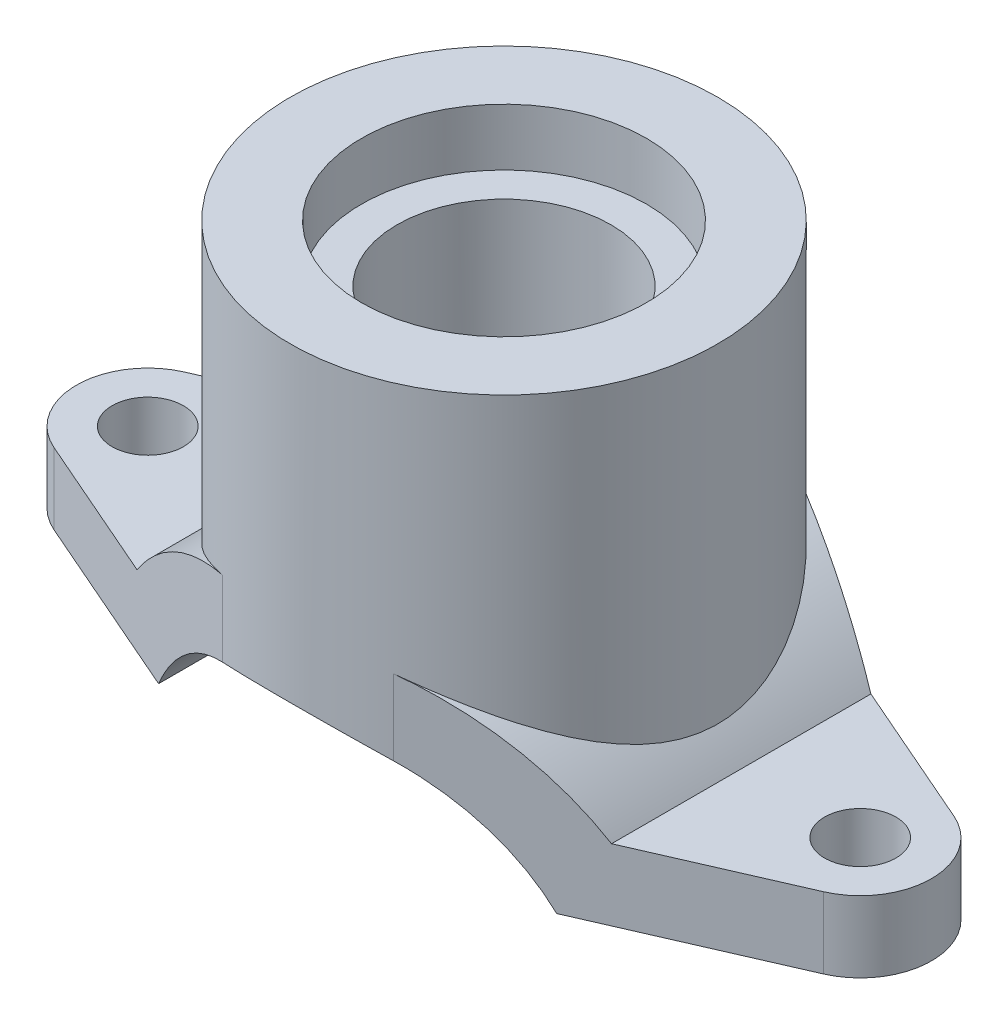
SolidWorks part; units mm, degrees
material "AISI 304"
ref_plane "Front Plane" through (0, 0, 0) normal (0, 0, 1) x (1, 0, 0)
ref_plane "Top Plane" through (0, 0, 0) normal (0, 1, 0) x (1, 0, 0)
ref_plane "Right Plane" through (0, 0, 0) normal (1, 0, 0) x (0, 0, -1)
sketch "Sketch2" plane through (0, 0, 0) normal (0, 0, 1) x (1, 0, 0)
  line L0 (0, 0) -> (0, 135.9633) construction
  line L1 (-150, 0) -> (-69.8498, 0)
  line L2 (69.8498, 0) -> (150, 0)
  line L3 (-150, 25) -> (-83.2406, 25)
  line L4 (83.2406, 25) -> (150, 25)
  line L5 (-150, 25) -> (-150, 0)
  line L6 (150, 25) -> (150, 0)
  arc A0 (69.8498, 0) -> (-69.8498, 0) centre (0, -39) ccw
  arc A1 (83.2406, 25) -> (-83.2406, 25) centre (0, -39) ccw
  dimension "D3" = 160
  dimension "D1" = 300
  dimension "D2" = 39
  dimension "D4" = 25
extrude "Boss-Extrude1" add sketch "Sketch2" along normal mid plane 150
sketch "Sketch3" plane through (0, 0, 0) normal (0, -1, 0) x (1, 0, 0)
  line L0 (-150, 0) -> (150, 0) construction
  line L1 (-150, 75) -> (-150, -75) construction
  line L2 (150, 75) -> (150, -75) construction
  line L3 (0, 0) -> (0, 89.4852) construction
  line L4 (-135, 22.9129) -> (-30, 68.7386)
  line L5 (-135, -22.9129) -> (-30, -68.7386)
  line L6 (135, -22.9129) -> (30, -68.7386)
  line L7 (135, 22.9129) -> (30, 68.7386)
  arc A0 (-30, -68.7386) -> (30, -68.7386) centre (0, 0) ccw
  arc A1 (-135, 22.9129) -> (-135, -22.9129) centre (-125, 0) ccw
  arc A2 (135, 22.9129) -> (135, -22.9129) centre (125, 0) cw
  arc A3 (30, 68.7386) -> (-30, 68.7386) centre (0, 0) ccw
  circle A4 centre (-125, 0) radius 12.5
  circle A5 centre (125, 0) radius 12.5
  dimension "D1" = 150
  dimension "D2" = 50
  dimension "D3" = 25
  dimension "D4" = 25
extrude "Cut-Extrude1" cut sketch "Sketch3" against normal blind 150 flip side to cut
ref_plane "Plane1" through (0, 150, 0) normal (0, -1, 0) x (-1, 0, 0)
sketch "Sketch4" plane through (0, 150, 0) normal (0, -1, 0) x (-1, 0, 0)
  circle A0 centre (0, 0) radius 75
  dimension "D1" = 150
extrude "Boss-Extrude2" add sketch "Sketch4" along normal up to next
sketch "Sketch6" plane through (0, 150, 0) normal (0, -1, 0) x (-1, 0, 0)
  circle A0 centre (0, 0) radius 37.5
  dimension "D1" = 75
extrude "Cut-Extrude2" cut sketch "Sketch6" along normal blind 150 contours A0
sketch "Sketch7" plane through (0, 150, 0) normal (0, -1, 0) x (-1, 0, 0)
  circle A0 centre (0, 0) radius 50
  dimension "D1" = 100
extrude "Cut-Extrude3" cut sketch "Sketch7" along normal blind 20 contours A0
